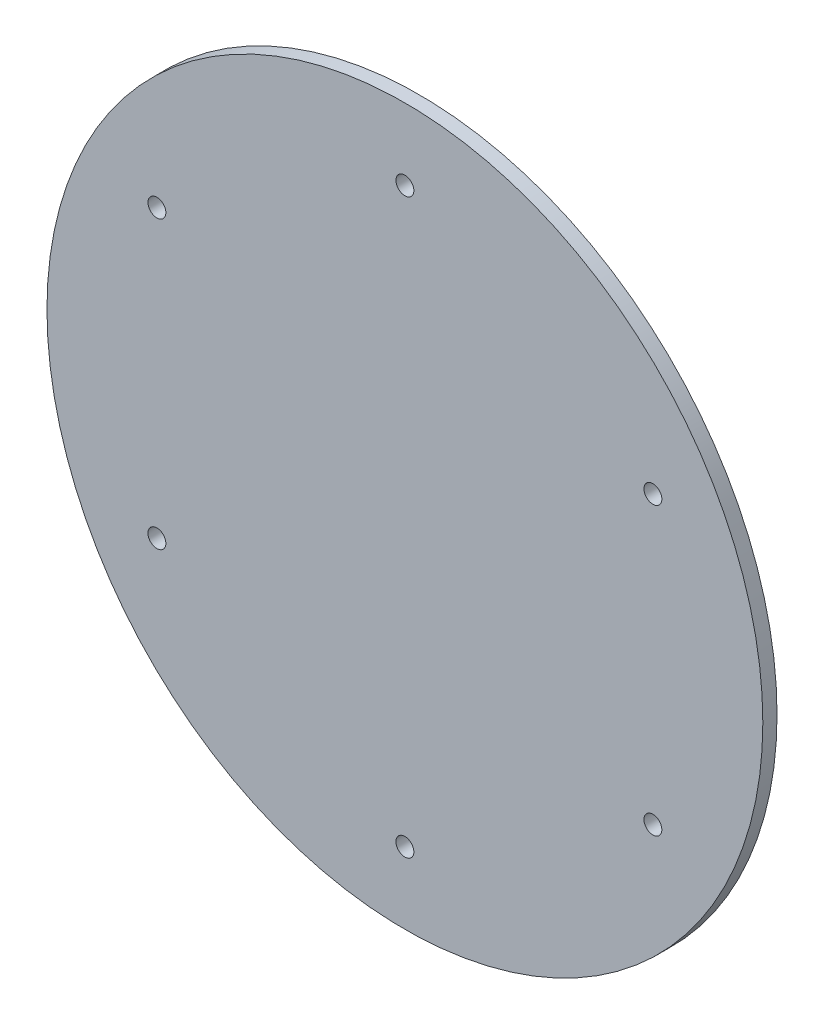
SolidWorks part; units mm, degrees
ref_plane "Front Plane" through (0, 0, 0) normal (0, 0, 1) x (1, 0, 0)
ref_plane "Top Plane" through (0, 0, 0) normal (0, 1, 0) x (1, 0, 0)
ref_plane "Right Plane" through (0, 0, 0) normal (1, 0, 0) x (0, 0, -1)
sketch "Sketch1" plane through (0, 0, 0) normal (0, 0, 1) x (1, 0, 0)
  circle A0 centre (0, 0) radius 80
  circle A1 centre (0, 64) radius 2
  circle A2 centre (55.4256, 32) radius 2
  circle A3 centre (55.4256, -32) radius 2
  circle A4 centre (0, -64) radius 2
  circle A5 centre (-55.4256, -32) radius 2
  circle A6 centre (-55.4256, 32) radius 2
  point P17 (0, 0)
  dimension "D1" = 160
  dimension "D2" = 4
  dimension "D3" = 64
  dimension "D4" = 6
extrude "Boss-Extrude1" add sketch "Sketch1" along normal blind 3.175
